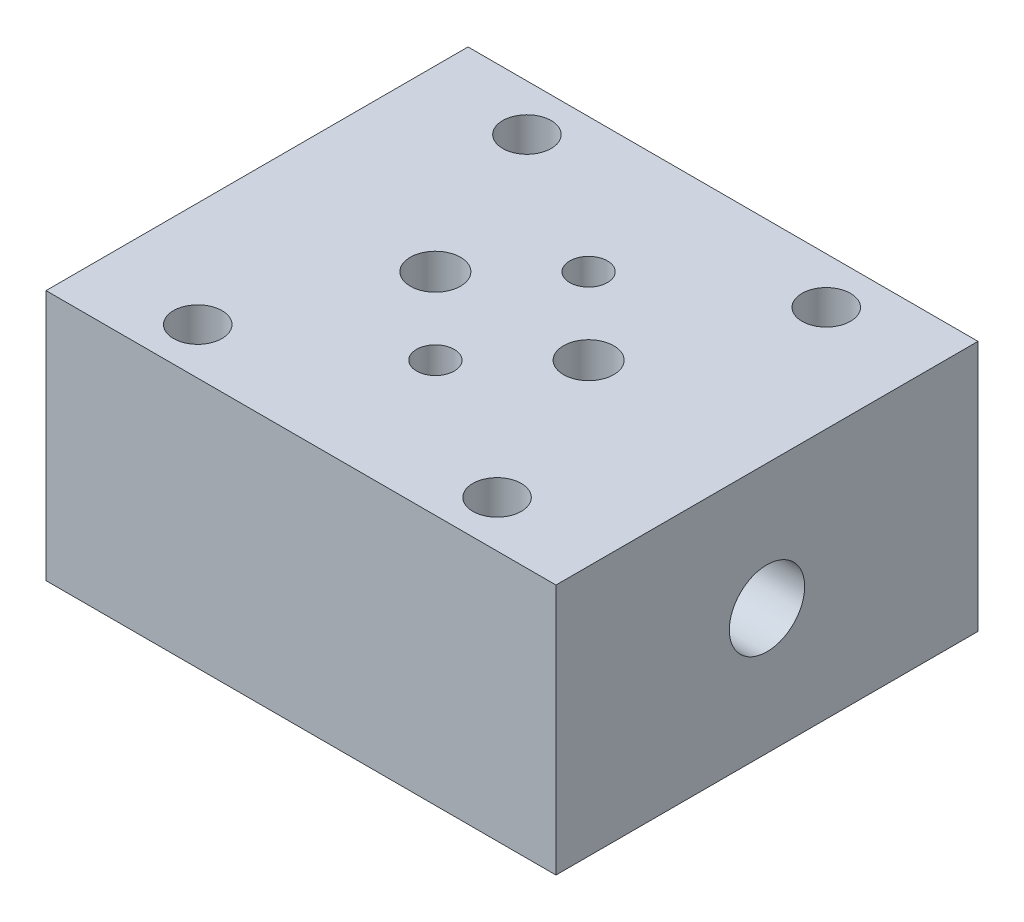
SolidWorks part; units mm, degrees
ref_plane "Front Plane" through (0, 0, 0) normal (0, 0, 1) x (1, 0, 0)
ref_plane "Top Plane" through (0, 0, 0) normal (0, 1, 0) x (1, 0, 0)
ref_plane "Right Plane" through (0, 0, 0) normal (1, 0, 0) x (0, 0, -1)
sketch "Sketch1" plane through (0, 0, 0) normal (0, 1, 0) x (1, 0, 0)
  line L1 (-6.9992, 10.3146) -> (33.6008, 10.3146)
  line L2 (-6.9992, 10.3146) -> (-6.9992, -23.2854)
  line L3 (-6.9992, -23.2854) -> (33.6008, -23.2854)
  line L4 (33.6008, 10.3146) -> (33.6008, -23.2854)
  dimension "D1" = 40.6
  dimension "D2" = 33.6
extrude "Extrude6" add sketch "Sketch1" along normal blind 20
sketch "Sketch7" plane through (0, 20, 0) normal (0, 1, 0) x (-1, 0, 0)
  line L0 (6.9992, 6.4854) -> (6.9992, -6.6196) construction
  line L1 (6.9992, -10.3146) -> (6.9992, 23.2854) construction
  line L3 (6.9992, 6.4854) -> (6.9992, 19.5904) construction
  line L4 (-13.3008, -10.3146) -> (-1.3858, -10.3146) construction
  line L5 (-33.6008, -10.3146) -> (6.9992, -10.3146) construction
  line L6 (-13.3008, -10.3146) -> (-25.2158, -10.3146) construction
  line L7 (-33.6008, 6.4854) -> (-33.6008, 0.3854)
  line L8 (-33.6008, 23.2854) -> (-33.6008, -10.3146) construction
  line L9 (-33.6008, 6.4854) -> (-33.6008, 12.5854) construction
  line L10 (-13.3008, 23.2854) -> (-19.4008, 23.2854) construction
  line L11 (6.9992, 23.2854) -> (-33.6008, 23.2854) construction
  line L12 (-13.3008, 23.2854) -> (-7.2008, 23.2854) construction
  circle A0 centre (-1.3858, -6.6196) radius 1.93
  circle A1 centre (-25.2158, -6.6196) radius 1.93
  circle A2 centre (-1.3858, 19.5904) radius 1.93
  circle A3 centre (-25.2158, 19.5904) radius 1.93
  dimension "D9" = 3.86
  dimension "D10" = 3.86
  dimension "D11" = 3.86
  dimension "D12" = 3.86
  dimension "D1" = 13.105
  dimension "D2" = 13.105
  dimension "D3" = 11.915
  dimension "D4" = 11.915
  dimension "D5" = 6.1
  dimension "D6" = 6.1
  dimension "D7" = 6.1
  dimension "D8" = 6.1
sketch "Sketch9" plane through (0, 20, 0) normal (0, 1, 0) x (1, 0, 0)
extrude "Extrude12" cut sketch "Sketch7" against normal through all contours A3 | A2 | A0 | A1
sketch "Sketch12" plane through (0, 20, 0) normal (0, 1, 0) x (1, 0, 0)
  line L0 (13.3008, 10.3146) -> (7.2008, 10.3146) construction
  line L1 (33.6008, 10.3146) -> (-6.9992, 10.3146) construction
  line L2 (13.3008, 10.3146) -> (19.4008, 10.3146) construction
  line L3 (33.6008, -6.4854) -> (33.6008, -0.3854) construction
  line L4 (33.6008, -23.2854) -> (33.6008, 10.3146) construction
  line L5 (33.6008, -6.4854) -> (33.6008, -12.5854) construction
  circle A0 centre (7.2008, -6.4854) radius 2
  circle A1 centre (13.3008, -0.3854) radius 1.5
  circle A2 centre (19.4008, -6.4854) radius 2
  circle A3 centre (13.3008, -12.5854) radius 1.5
  dimension "D5" = 3
  dimension "D6" = 3
  dimension "D7" = 4
  dimension "D8" = 4
  dimension "D1" = 6.1
  dimension "D2" = 6.1
  dimension "D3" = 6.1
  dimension "D4" = 6.1
extrude "Extrude13" cut sketch "Sketch12" against normal blind 15 contours A3 | A1 | A0 | A2
sketch "Sketch13" plane through (33.6008, 0, 0) normal (1, 0, 0) x (0, 0, -1)
  line L2 (10.3146, 10) -> (-23.2854, 10)
  line L3 (10.3146, 20) -> (10.3146, 0) construction
  line L4 (-23.2854, 20) -> (-23.2854, 0) construction
  circle A0 centre (-6.4854, 10) radius 3
  dimension "D1" = 6
extrude "Extrude14" cut sketch "Sketch13" against normal blind 14.2 contours A0
